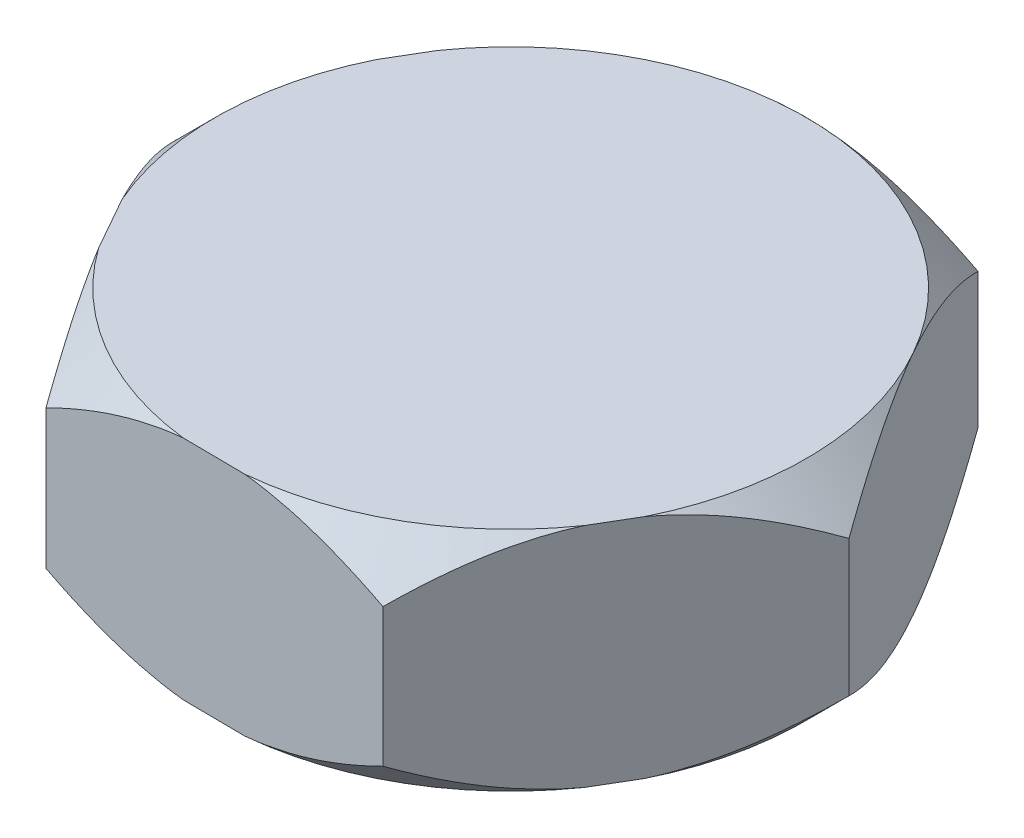
SolidWorks part; units mm, degrees
ref_plane "前视基准面" through (0, 0, 0) normal (0, 0, 1) x (1, 0, 0)
ref_plane "上视基准面" through (0, 0, 0) normal (0, 1, 0) x (1, 0, 0)
ref_plane "右视基准面" through (0, 0, 0) normal (1, 0, 0) x (0, 0, -1)
other "Configuration Table"
sketch "草图1" plane through (0, 0, 0) normal (0, 1, 0) x (1, 0, 0)
  line L1 (-1.5209, -2.5763) -> (1.4791, -2.6054)
  line L2 (1.4791, -2.6054) -> (3.0042, -0.0218)
  line L3 (3.0042, -0.0218) -> (1.5294, 2.5908)
  line L4 (1.5294, 2.5908) -> (-1.4706, 2.6198)
  line L5 (-1.4706, 2.6198) -> (-2.9958, 0.0363)
  line L6 (-2.9958, 0.0363) -> (-1.5209, -2.5763)
  circle A0 centre (0.0042, 0.0072) radius 2.5982 construction
  dimension "D1" = 3
extrude "凸台-拉伸1" add sketch "草图1" along normal mid plane 2
sketch "草图2" plane through (0, 1, 0) normal (0, 1, 0) x (1, 0, 0)
  line L6 (-2.9958, 0.0363) -> (-1.5209, -2.5763)
  line L7 (-1.5209, -2.5763) -> (1.4791, -2.6054)
  line L8 (1.4791, -2.6054) -> (3.0042, -0.0218)
  line L9 (3.0042, -0.0218) -> (1.5294, 2.5908)
  line L10 (1.5294, 2.5908) -> (-1.4706, 2.6198)
  line L11 (-1.4706, 2.6198) -> (-2.9958, 0.0363)
  line L12 (-2.9958, 0.0363) -> (-1.5209, -2.5763)
  line L13 (-1.5209, -2.5763) -> (1.4791, -2.6054)
  line L14 (1.4791, -2.6054) -> (3.0042, -0.0218)
  line L15 (3.0042, -0.0218) -> (1.5294, 2.5908)
  line L16 (1.5294, 2.5908) -> (-1.4706, 2.6198)
  line L17 (-1.4706, 2.6198) -> (-2.9958, 0.0363)
  circle A0 centre (0, 0) radius 2.6055
  point P6 (0, 0)
  dimension "D1" = 0
extrude "切除-拉伸1" cut sketch "草图2" against normal through all draft 45 flip side to cut contours L13 A0 L14 L17 L12
mirror "镜向1" about plane through (0, 0, 0) normal (0, 1, 0) of "切除-拉伸1"
